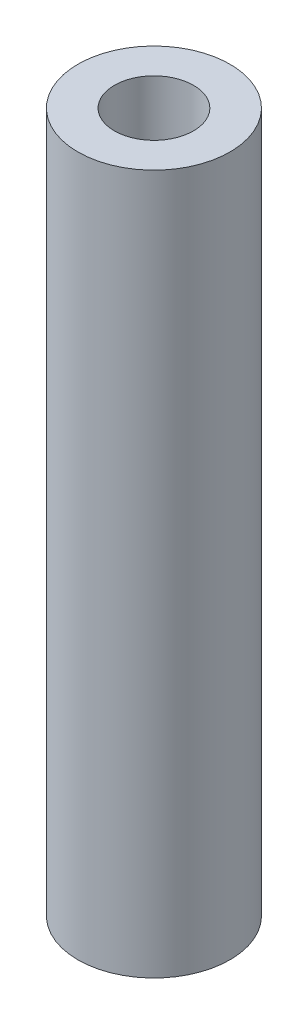
SolidWorks part; units mm, degrees
ref_plane "Front Plane" through (0, 0, 0) normal (0, 0, 1) x (1, 0, 0)
ref_plane "Top Plane" through (0, 0, 0) normal (0, 1, 0) x (1, 0, 0)
ref_plane "Right Plane" through (0, 0, 0) normal (1, 0, 0) x (0, 0, -1)
sketch "Sketch1" plane through (0, 0, 0) normal (0, 1, 0) x (1, 0, 0)
  circle A0 centre (0, 0) radius 5
  circle A1 centre (0, 0) radius 2.6
  point P5 (-0.344, 0)
  dimension "D1" = 10
  dimension "D2" = 5.2
extrude "Boss-Extrude1" add sketch "Sketch1" along normal blind 46
